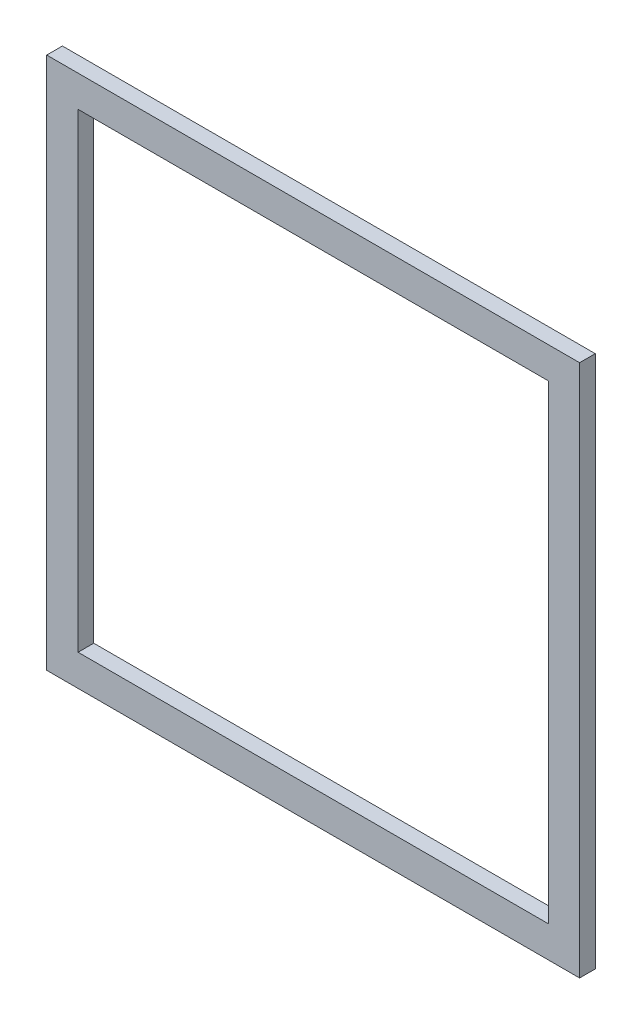
SolidWorks part; units mm, degrees
ref_plane "Plan de face" through (0, 0, 0) normal (0, 0, 1) x (1, 0, 0)
ref_plane "Plan de dessus" through (0, 0, 0) normal (0, 1, 0) x (1, 0, 0)
ref_plane "Plan de droite" through (0, 0, 0) normal (1, 0, 0) x (0, 0, -1)
sketch "Esquisse2" plane through (0, 0, 0) normal (0, 0, 1) x (1, 0, 0)
  line L1 (-17, -17) -> (17, -17)
  line L2 (-17, -17) -> (-17, 17)
  line L3 (-17, 17) -> (17, 17)
  line L4 (17, -17) -> (17, 17)
  line L5 (-17, -17) -> (17, 17) construction
  line L6 (-17, 17) -> (17, -17) construction
  line L7 (-15, -15) -> (15, -15)
  line L8 (-15, -15) -> (-15, 15)
  line L9 (-15, 15) -> (15, 15)
  line L10 (15, -15) -> (15, 15)
  line L11 (-15, -15) -> (15, 15) construction
  line L12 (-15, 15) -> (15, -15) construction
  point P0 (0, 0)
  point P6 (0, 0)
  dimension "D1" = 34
  dimension "D2" = 34
  dimension "D3" = 30
extrude "Boss.-Extru.1" add sketch "Esquisse2" along normal blind 1
